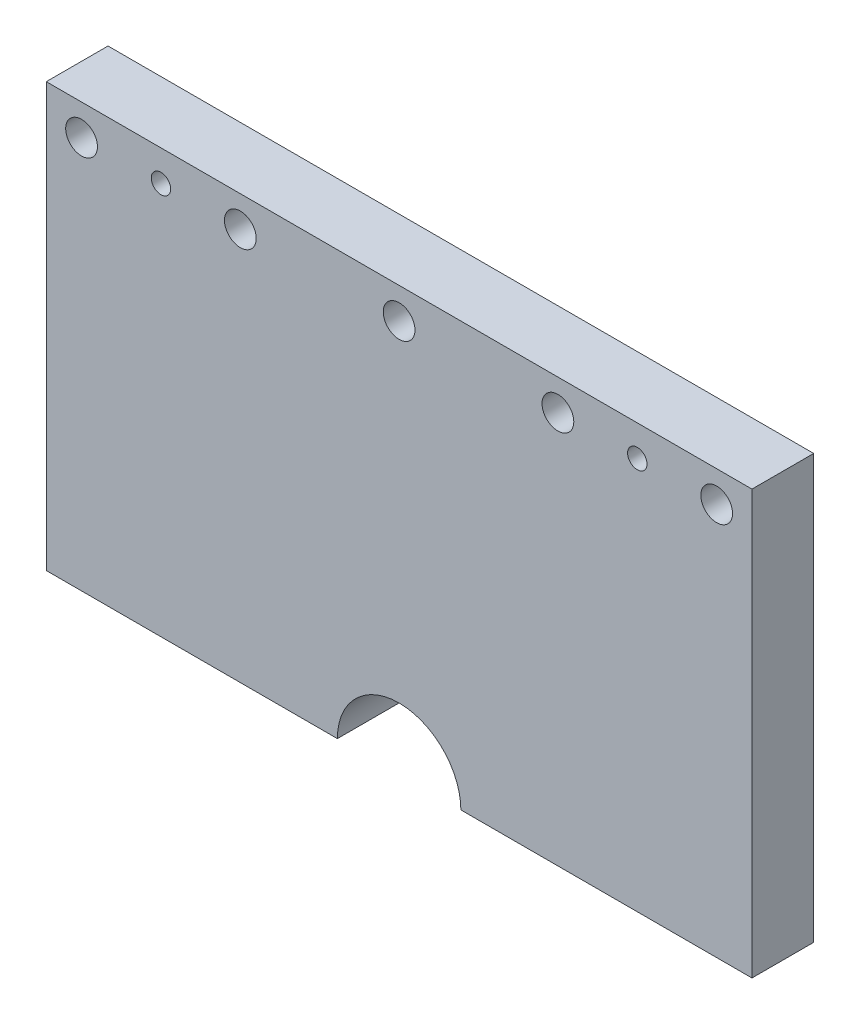
SolidWorks part; units mm, degrees
ref_plane "Plano frontal" through (0, 0, 0) normal (0, 0, 1) x (1, 0, 0)
ref_plane "Plano superior" through (0, 0, 0) normal (0, 1, 0) x (1, 0, 0)
ref_plane "Plano direito" through (0, 0, 0) normal (1, 0, 0) x (0, 0, -1)
sketch "Esboço1" plane through (0, 0, 0) normal (0, 0, 1) x (1, 0, 0)
  line L1 (-200, -35) -> (-200, 0) construction
  line L2 (200, 0) -> (-200, 0)
  line L3 (200, 0) -> (200, -240)
  line L4 (200, -240) -> (-200, -240)
  line L5 (-200, 0) -> (-200, -240)
  dimension "D1" = 240
extrude "Ressalto-extrusão1" add sketch "Esboço1" along normal blind 35
sketch "Esboço2" plane through (0, 0, 0) normal (0, 0, -1) x (-1, 0, 0)
  line L1 (-200, -240) -> (-200, 0) construction
  line L2 (200, -240) -> (-200, -240) construction
  circle A1 centre (0, -240) radius 35
  dimension "D1" = 200
extrude "Corte-extrusão1" cut sketch "Esboço2" against normal through all
hole_wizard "Furo roscado de M101" positions "Esboço3" profile "Esboço4" tap size "M10" standard "DIN"
sketch "Esboço3" plane through (0, -240, 0) normal (0, -1, 0) x (-1, 0, 0)
  point P0 (-180, -17.5)
  point P3 (-80, -17.5)
  point P6 (80, -17.5)
  point P9 (180, -17.5)
sketch "Esboço4" plane through (180, -240, 17.5) normal (1, 0, 0) x (0, 0, -1)
  line L0 (0, 0) -> (0, 30.0537)
  line L1 (0, 30.0537) -> (4.25, 27.5)
  line L2 (4.25, 27.5) -> (4.25, 0)
  line L5 (4.25, 0) -> (0, 0)
  line L10 (0, 30.0537) -> (-4.25, 27.5) construction
  line L11 (0, -6.35) -> (0, 107.95) construction
  dimension "Tap Drill Dia." = 8.5
  dimension "Tap Drill Depth" = 27.5
  dimension "Drill Angle" = 118
cosmetic thread "Rosca de furo1" parameters "D1"=20, "D2"=10
cosmetic thread "Rosca de furo2" parameters "D1"=20, "D2"=10
cosmetic thread "Rosca de furo3" parameters "D1"=20, "D2"=10
cosmetic thread "Rosca de furo4" parameters "D1"=20, "D2"=10
hole_wizard "Furos-guia com Ø10.0mm1" positions "Esboço5" profile "Esboço6" hole size "Ø10.0" standard "DIN"
sketch "Esboço5" plane through (0, -240, 0) normal (0, -1, 0) x (-1, 0, 0)
  point P0 (-130, -17.5)
  point P3 (130, -17.5)
sketch "Esboço6" plane through (130, -240, 17.5) normal (1, 0, 0) x (0, 0, -1)
  line L0 (0, 0) -> (0, 30.5043)
  line L1 (0, 30.5043) -> (5, 27.5)
  line L2 (5, 27.5) -> (5, 0)
  line L5 (5, 0) -> (0, 0)
  line L10 (0, 30.5043) -> (-5, 27.5) construction
  line L11 (0, -6.35) -> (0, 107.95) construction
  dimension "Hole Dia." = 10
  dimension "Hole Depth" = 27.5
  dimension "Drill Angle" = 118
hole_wizard "Rebaixo para parafuso Allen sextavado de M101" positions "Esboço9" profile "Esboço10" counterbore size "M10" standard "DIN" end condition through all
sketch "Esboço9" plane through (0, 0, 35) normal (0, 0, 1) x (1, 0, 0)
  point P0 (180, -17.5)
  point P3 (90, -17.5)
  point P6 (0, -17.5)
  point P9 (-90, -17.5)
  point P12 (-180, -17.5)
sketch "Esboço10" plane through (180, -17.5, 35) normal (1, 0, 0) x (0, -1, 0)
  line L0 (0, 0) -> (0, 35)
  line L1 (0, 35) -> (5.5, 35)
  line L3 (5.5, 35) -> (5.5, 15)
  line L4 (5.5, 15) -> (9, 15)
  line L5 (9, 15) -> (9, 0)
  line L7 (9, 0) -> (0, 0)
  line L11 (0, -6.35) -> (0, 107.95) construction
  dimension "Thru Hole Dia." = 11
  dimension "Thru Hole Depth" = 35
  dimension "C'Bore Dia." = 18
  dimension "C'Bore Depth" = 15
hole_wizard "Furos-guia com Ø10.0mm2" positions "Esboço11" profile "Esboço12" hole size "Ø10.0" standard "DIN" end condition through all
sketch "Esboço11" plane through (0, 0, 35) normal (0, 0, 1) x (1, 0, 0)
  point P0 (135, -17.5)
  point P3 (-135, -17.5)
sketch "Esboço12" plane through (135, -17.5, 35) normal (1, 0, 0) x (0, -1, 0)
  line L0 (0, 0) -> (0, 35)
  line L1 (0, 35) -> (5, 35)
  line L2 (5, 35) -> (5, 0)
  line L5 (5, 0) -> (0, 0)
  line L11 (0, -6.35) -> (0, 107.95) construction
  dimension "Thru Hole Dia." = 10
  dimension "Thru Hole Depth" = 35
hole_wizard "Furo de diâmetro Ø11.0 (11)1" positions "Esboço13" profile "Esboço14" hole size "Ø11.0" standard "DIN"
sketch "Esboço13" plane through (0, 0, 35) normal (0, 0, 1) x (1, 0, 0)
  point P0 (135, -17.5)
  point P3 (-135, -17.5)
sketch "Esboço14" plane through (135, -17.5, 35) normal (1, 0, 0) x (0, -1, 0)
  line L0 (0, 0) -> (0, 18.3047)
  line L1 (0, 18.3047) -> (5.5, 15)
  line L2 (5.5, 15) -> (5.5, 0)
  line L5 (5.5, 0) -> (0, 0)
  line L10 (0, 18.3047) -> (-5.5, 15) construction
  line L11 (0, -6.35) -> (0, 107.95) construction
  dimension "Hole Dia." = 11
  dimension "Hole Depth" = 15
  dimension "Drill Angle" = 118
